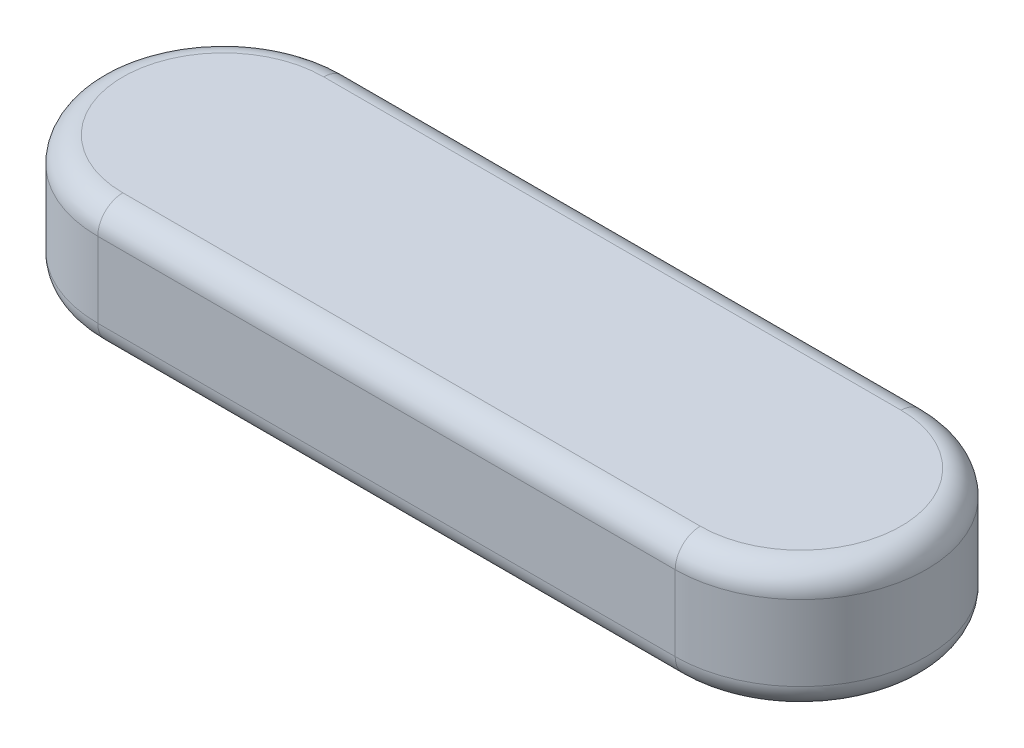
SolidWorks part; units mm, degrees
ref_plane "Front Plane" through (0, 0, 0) normal (0, 0, 1) x (1, 0, 0)
ref_plane "Top Plane" through (0, 0, 0) normal (0, 1, 0) x (1, 0, 0)
ref_plane "Right Plane" through (0, 0, 0) normal (1, 0, 0) x (0, 0, -1)
sketch "Sketch2" plane through (0, 0, 0) normal (0, 1, 0) x (1, 0, 0)
  line L0 (-11.5, 0) -> (11.5, 0) construction
  line L1 (-11.5, 5) -> (11.5, 5)
  line L2 (-11.5, -5) -> (11.5, -5)
  arc A0 (-11.5, 5) -> (-11.5, -5) centre (-11.5, 0) ccw
  arc A1 (11.5, -5) -> (11.5, 5) centre (11.5, 0) ccw
  point P3 (0, 0)
  dimension "D1" = 0
  dimension "D2" = 23
  dimension "D3" = 10
extrude "Boss-Extrude1" add sketch "Sketch2" along normal blind 5
fillet "Fillet1" radius 1 8 edges at (-16.5, 0, 0) (0, 0, -5) (16.5, 0, 0) (-16.5, 5, 0) (0, 5, -5) (16.5, 5, 0) (0, 0, 5) (0, 5, 5)
